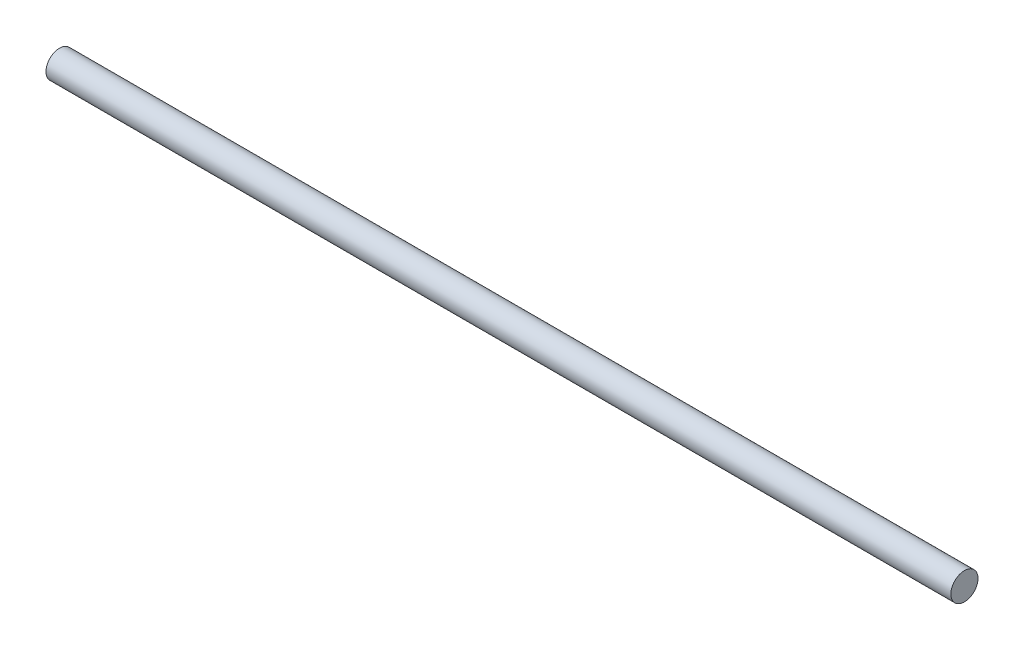
SolidWorks part; units mm, degrees
ref_plane "Alzado" through (0, 0, 0) normal (0, 0, 1) x (1, 0, 0)
ref_plane "Planta" through (0, 0, 0) normal (0, 1, 0) x (1, 0, 0)
ref_plane "Vista lateral" through (0, 0, 0) normal (1, 0, 0) x (0, 0, -1)
sketch "Croquis1" plane through (0, 0, 0) normal (1, 0, 0) x (0, 0, -1)
  circle A0 centre (0, 0) radius 7.5
  dimension "D1" = 15
extrude "Saliente-Extruir1" add sketch "Croquis1" along normal mid plane 500
